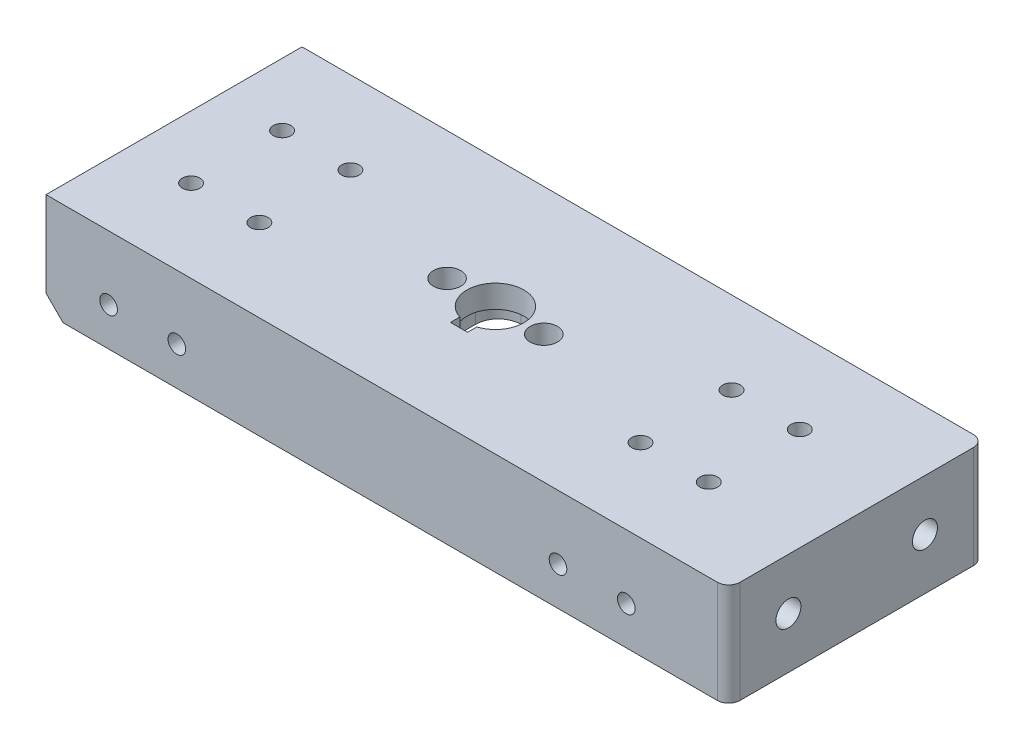
SolidWorks part; units mm, degrees
material "6061-T6 (SS)"
ref_plane "Front Plane" through (0, 0, 0) normal (0, 0, 1) x (1, 0, 0)
ref_plane "Top Plane" through (0, 0, 0) normal (0, 1, 0) x (1, 0, 0)
ref_plane "Right Plane" through (0, 0, 0) normal (1, 0, 0) x (0, 0, -1)
sketch "Sketch1" plane through (0, 0, 0) normal (0, 1, 0) x (1, 0, 0)
  line L1 (0, 0) -> (113, 0)
  line L2 (0, 0) -> (0, 45)
  line L3 (0, 45) -> (113, 45)
  line L4 (113, 0) -> (113, 45)
  dimension "D1" = 45
  dimension "D2" = 113
extrude "Boss-Extrude1" add sketch "Sketch1" along normal blind 4
sketch "Sketch4" plane through (0, 4, 0) normal (0, 1, 0) x (1, 0, 0)
  line L0 (56.5, 45) -> (56.5, -12.4802) construction
  line L1 (113, 45) -> (0, 45) construction
  line L3 (0, 22.5) -> (122.1673, 22.5) construction
  line L4 (0, 45) -> (0, 0) construction
  point P0 (11, 30.5)
  point P12 (23, 30.5)
  point P13 (23, 14.5)
  point P14 (11, 14.5)
  point P25 (102, 14.5)
  point P26 (90, 14.5)
  point P27 (90, 30.5)
  point P28 (102, 30.5)
  dimension "D1" = 2
  dimension "D3" = 12
  dimension "D4" = 16
  dimension "D5" = 8
  dimension "D6" = 79
  dimension "D2" = 2
hole_wizard "M2.5 Clearance Hole2" positions "Sketch4" profile "Sketch3" hole size "M2.5" standard "DIN" end condition through all
sketch "Sketch3" plane through (11, 4, -30.5) normal (1, 0, 0) x (0, 0, 1)
  line L0 (0, 0) -> (0, 4)
  line L1 (0, 4) -> (1.55, 4)
  line L2 (1.55, 4) -> (1.55, 0)
  line L5 (1.55, 0) -> (0, 0)
  line L11 (0, -6.35) -> (0, 107.95) construction
  dimension "Thru Hole Dia." = 3.1
  dimension "Thru Hole Depth" = 4
sketch "Sketch5" plane through (0, 0, 0) normal (0, -1, 0) x (1, 0, 0)
  line L0 (0, -22.5) -> (113, -22.5) construction
  line L1 (0, 0) -> (113, 0)
  line L3 (0, -45) -> (113, -45)
  line L5 (0, -8.175) -> (113, -8.175)
  line L7 (0, -36.825) -> (113, -36.825)
  line L9 (0, -22.5) -> (113, -22.5) construction
  line L20 (0, 0) -> (0, -8.175)
  line L23 (0, -45) -> (0, -36.825)
  line L24 (113, 0) -> (113, -8.175)
  line L25 (113, -36.825) -> (113, -45)
  line L26 (113, 0) -> (113, -45) construction
  line L27 (0, -45) -> (0, 0) construction
  dimension "D1" = 28.65
  dimension "D2" = 180
extrude "Boss-Extrude2" add sketch "Sketch5" along normal blind 14
sketch "Sketch7" plane through (0, -14, 0) normal (0, -1, 0) x (1, 0, 0)
  line L1 (0, -8.175) -> (113, -8.175) construction
  line L2 (34.5, -8.175) -> (78.5, -8.175)
  line L3 (34.5, -8.175) -> (34.5, -36.825)
  line L5 (113, -36.825) -> (0, -36.825) construction
  line L6 (34.5, -36.825) -> (78.5, -36.825)
  line L21 (78.5, -8.175) -> (78.5, -36.825)
  line L22 (113, -36.825) -> (0, -36.825) construction
  point P10 (56.5, -36.825)
  dimension "D1" = 44
extrude "Boss-Extrude3" add sketch "Sketch7" against normal up to next
sketch "Sketch10" plane through (0, 0, -45) normal (0, 0, -1) x (-1, 0, 0)
  line L1 (0, 0) -> (-34.5, 0) construction
  line L2 (-23, -7.25) -> (-11, -7.25)
  line L4 (-9.55, 1.1) -> (-12.45, 1.1)
  line L5 (-11, 1.1) -> (-11, -7.25)
  line L8 (-56.5, 4) -> (-56.5, -40.6573) construction
  line L9 (-113, 4) -> (0, 4) construction
  point P0 (-11, -7.25)
  point P2 (-23, -7.25)
  point P30 (-102, -7.25)
  point P31 (-90, -7.25)
  dimension "D1" = 7.25
  dimension "D2" = 12
hole_wizard "M2.5 Clearance Hole1" positions "Sketch10" profile "Sketch9" hole size "M2.5" standard "DIN" end condition through all
sketch "Sketch9" plane through (11, -7.25, -45) normal (1, 0, 0) x (0, 1, 0)
  line L0 (0, 0) -> (0, 45)
  line L1 (0, 45) -> (1.55, 45)
  line L2 (1.55, 45) -> (1.55, 0)
  line L5 (1.55, 0) -> (0, 0)
  line L11 (0, -6.35) -> (0, 107.95) construction
  dimension "Thru Hole Dia." = 3.1
  dimension "Thru Hole Depth" = 45
sketch "Sketch11" plane through (0, -14, 0) normal (0, -1, 0) x (1, 0, 0)
  line L24 (39.5, -5) -> (39.5, -40)
  line L25 (39.5, -40) -> (73.5, -40)
  line L26 (73.5, -40) -> (73.5, -5)
  line L27 (73.5, -5) -> (39.5, -5)
  line L28 (39.5, -5) -> (39.5, -40)
  line L29 (39.5, -40) -> (73.5, -40)
  line L30 (73.5, -40) -> (73.5, -5)
  line L31 (73.5, -5) -> (39.5, -5)
  dimension "D1" = 5
extrude "Cut-Extrude1" cut sketch "Sketch11" against normal blind 14
sketch "Sketch14" plane through (0, 4, 0) normal (0, 1, 0) x (1, 0, 0)
  line L0 (0, 45) -> (113, 0)
  line L1 (113, 0) -> (113, 45)
  line L2 (113, 45) -> (0, 0)
  point P12 (56.5, 22.5)
hole_wizard "Ø10.0mm Dowel Hole1" positions "Sketch14" profile "Sketch13" hole size "Ø10.0" standard "DIN" end condition through all
sketch "Sketch13" plane through (56.5, 4, -22.5) normal (1, 0, 0) x (0, 0, 1)
  line L0 (0, 0) -> (0, 18)
  line L1 (0, 18) -> (5, 18)
  line L2 (5, 18) -> (5, 0)
  line L5 (5, 0) -> (0, 0)
  line L11 (0, -6.35) -> (0, 107.95) construction
  dimension "Thru Hole Dia." = 10
  dimension "Thru Hole Depth" = 18
fillet "Fillet1" radius 4 4 edges at (39.5, -7, -40) (39.5, -7, -5) (73.5, -7, -5) (73.5, -7, -40)
sketch "Sketch15" plane through (0, -14, 0) normal (0, -1, 0) x (1, 0, 0)
  line L0 (0, -8.175) -> (34.5, -8.175) construction
  line L1 (34.5, -8.175) -> (34.5, -36.825) construction
  line L2 (78.5, -8.175) -> (78.5, -36.825) construction
  line L3 (34.5, -36.825) -> (0, -36.825) construction
  line L4 (78.5, -8.175) -> (113, -8.175) construction
  line L5 (113, -36.825) -> (78.5, -36.825) construction
  circle A0 centre (34.5, -9.775) radius 1.6
  circle A1 centre (34.5, -35.225) radius 1.6
  circle A2 centre (78.5, -9.775) radius 1.6
  circle A3 centre (78.5, -35.225) radius 1.6
  dimension "D1" = 3.2
extrude "Cut-Extrude2" cut sketch "Sketch15" against normal up to surface (14 mm away) and the other way through all up to face at (17.25, 0, -22.5)
fillet "Fillet2" radius 3.2 4 edges at (78.5, -7, -33.625) (78.5, -7, -11.375) (34.5, -7, -33.625) (34.5, -7, -11.375)
chamfer "Chamfer1" distance 3 angle 45 4 edges at (113, -14, -40.9125) (113, -14, -4.0875) (0, -14, -40.9125) (0, -14, -4.0875)
sketch "Sketch20" plane through (0, 0, 0) normal (0, -1, 0) x (1, 0, 0)
  line L1 (55, -17.7303) -> (58, -17.7303)
  line L2 (55, -17.7303) -> (55, -16.1)
  line L3 (55, -16.1) -> (58, -16.1)
  line L4 (58, -17.7303) -> (58, -16.1)
  circle A0 centre (56.5, -22.5) radius 5 construction
  point P6 (56.5, -17.5)
  dimension "D1" = 1.4
  dimension "D2" = 3
extrude "Cut-Extrude4" cut sketch "Sketch20" against normal through all
sketch "Sketch23" plane through (0, 0, 0) normal (0, -1, 0) x (-1, 0, 0)
  circle A0 centre (-56.5, 22.5) radius 8.5
  point P4 (-65, 22.5)
  point P6 (-48, 22.5)
  dimension "D1" = 17
hole_wizard "M4 Clearance Hole2" positions "Sketch23" profile "Sketch22" hole size "M4" standard "DIN" end condition through all
sketch "Sketch22" plane through (48, 0, -22.5) normal (1, 0, 0) x (0, 0, -1)
  line L0 (0, 0) -> (0, 4)
  line L1 (0, 4) -> (2.4, 4)
  line L2 (2.4, 4) -> (2.4, 0)
  line L5 (2.4, 0) -> (0, 0)
  line L11 (0, -6.35) -> (0, 107.95) construction
  dimension "Thru Hole Dia." = 4.8
  dimension "Thru Hole Depth" = 4
sketch "Sketch24" [suppressed] plane through (0, 0, 0) normal (0, -1, 0) x (1, 0, 0)
  line L8 (39.5, -8) -> (39.5, -24.5)
  line L9 (42.5, -27.5) -> (70.5, -27.5)
  line L10 (73.5, -24.5) -> (73.5, -8)
  line L11 (70.5, -5) -> (42.5, -5)
  line L12 (39.5, -8) -> (39.5, -24.5)
  line L13 (42.5, -27.5) -> (70.5, -27.5)
  line L14 (73.5, -24.5) -> (73.5, -8)
  line L15 (70.5, -5) -> (42.5, -5)
  circle A0 centre (48, -16.25) radius 3.25
  circle A1 centre (65, -16.25) radius 3.25
  arc A10 (39.5, -24.5) -> (42.5, -27.5) centre (42.5, -24.5) ccw
  arc A11 (70.5, -27.5) -> (73.5, -24.5) centre (70.5, -24.5) ccw
  arc A12 (73.5, -8) -> (70.5, -5) centre (70.5, -8) ccw
  arc A13 (42.5, -5) -> (39.5, -8) centre (42.5, -8) ccw
  arc A14 (39.5, -24.5) -> (42.5, -27.5) centre (42.5, -24.5) ccw
  arc A15 (70.5, -27.5) -> (73.5, -24.5) centre (70.5, -24.5) ccw
  arc A16 (73.5, -8) -> (70.5, -5) centre (70.5, -8) ccw
  arc A17 (42.5, -5) -> (39.5, -8) centre (42.5, -8) ccw
  dimension "D1" = 6.5
  dimension "D2" = 1
extrude "Boss-Extrude4" [suppressed] add sketch "Sketch24" along normal blind 10 separate body
sketch "Sketch27" [suppressed] plane through (0, -10, 0) normal (0, -1, 0) x (-1, 0, 0)
  point P0 (-56.5, 16.25)
hole_wizard "M4 Clearance Hole3" [suppressed] positions "Sketch27" profile "Sketch26" hole size "M4" standard "DIN"
sketch "Sketch26" plane through (56.5, -10, -16.25) normal (1, 0, 0) x (0, 0, -1)
  line L0 (0, 0) -> (0, 10.001)
  line L1 (0, 10.001) -> (2.25, 10.001)
  line L2 (2.25, 10.001) -> (2.25, 0)
  line L5 (2.25, 0) -> (0, 0)
  line L11 (0, -6.35) -> (0, 107.95) construction
  dimension "Thru Hole Dia." = 4.5
  dimension "Thru Hole Depth" = 10.001
sketch "Sketch28" plane through (113, 0, 0) normal (1, 0, 0) x (0, 0, -1)
  line L0 (45, -14) -> (45, -11) construction
  line L1 (36.825, -11) -> (36.825, -14) construction
  line L2 (36.825, -14) -> (45, -14) construction
  line L3 (8.175, -14) -> (8.175, -11) construction
  line L4 (0, -11) -> (0, -14) construction
  line L5 (0, -14) -> (8.175, -14) construction
  line L6 (36.825, 0) -> (36.825, -11) construction
  line L7 (45, -11) -> (45, 4) construction
  line L8 (45, 4) -> (0, 4) construction
  line L9 (0, 4) -> (0, -11) construction
  line L10 (8.175, -11) -> (8.175, 0) construction
  line L11 (8.175, 0) -> (36.825, 0) construction
  line L12 (45, -14) -> (45, -11)
  line L13 (36.825, -11) -> (36.825, -14)
  line L14 (36.825, -14) -> (45, -14)
  line L15 (8.175, -14) -> (8.175, -11)
  line L16 (0, -11) -> (0, -14)
  line L17 (0, -14) -> (8.175, -14)
  line L18 (36.825, 0) -> (36.825, -11)
  line L19 (45, -11) -> (45, 4)
  line L20 (45, 4) -> (0, 4)
  line L21 (0, 4) -> (0, -11)
  line L22 (8.175, -11) -> (8.175, 0)
  line L23 (8.175, 0) -> (36.825, 0)
extrude "Boss-Extrude5" add sketch "Sketch28" along normal blind 2 and the other way blind 3
sketch "Sketch29" plane through (115, 0, 0) normal (1, 0, 0) x (0, 0, -1)
  line L1 (0, 4) -> (45, 4)
  line L2 (0, 4) -> (0, -14)
  line L3 (0, -14) -> (45, -14)
  line L4 (45, 4) -> (45, -14)
extrude "Boss-Extrude6" add sketch "Sketch29" along normal blind 5
chamfer "Chamfer2" distance 1.75 angle 45 3 edges at (115, -7, -8.175) (115, -7, -36.825)
sketch "Sketch32" plane through (120, 0, 0) normal (1, 0, 0) x (0, 0, -1)
  line L0 (0, -5) -> (45, -5) construction
  line L1 (0, 4) -> (0, -14) construction
  line L2 (45, -14) -> (45, 4) construction
  point P9 (10.5, -5)
  point P11 (34.5, -5)
  point P13 (22.5, -5)
  dimension "D1" = 24
  dimension "D2" = 12
hole_wizard "Ø4.4 (4.4) Diameter Hole1" positions "Sketch32" profile "Sketch31" hole size "Ø4.4" standard "DIN"
sketch "Sketch31" plane through (120, -5, -34.5) normal (0, 1, 0) x (0, 0, -1)
  line L0 (0, 0) -> (0, 5)
  line L1 (0, 5) -> (2.2, 5)
  line L2 (2.2, 5) -> (2.2, 0)
  line L5 (2.2, 0) -> (0, 0)
  line L11 (0, -6.35) -> (0, 107.95) construction
  dimension "Thru Hole Dia." = 4.4
  dimension "Thru Hole Depth" = 5
fillet "Fillet3" radius 2 2 edges at (120, -5, 0) (120, -5, -45)
